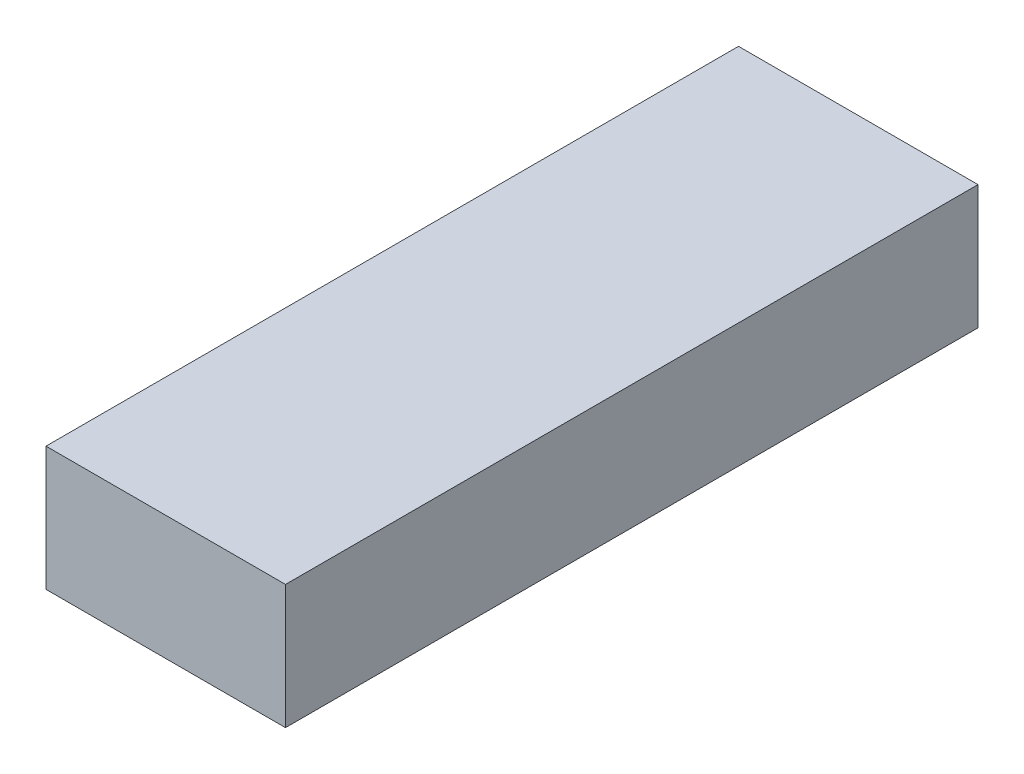
SolidWorks part; units mm, degrees
ref_plane "Front Plane" through (0, 0, 0) normal (0, 0, 1) x (1, 0, 0)
ref_plane "Top Plane" through (0, 0, 0) normal (0, 1, 0) x (1, 0, 0)
ref_plane "Right Plane" through (0, 0, 0) normal (1, 0, 0) x (0, 0, -1)
sketch "Sketch1" plane through (0, 0, 0) normal (0, 0, 1) x (1, 0, 0)
  line L1 (-16.6, -8.6) -> (16.6, -8.6)
  line L2 (-16.6, -8.6) -> (-16.6, 8.6)
  line L3 (-16.6, 8.6) -> (16.6, 8.6)
  line L4 (16.6, -8.6) -> (16.6, 8.6)
  line L5 (-16.6, -8.6) -> (16.6, 8.6) construction
  line L6 (-16.6, 8.6) -> (16.6, -8.6) construction
  point P0 (0, 0)
  dimension "D1" = 33.2
  dimension "D2" = 17.2
extrude "Boss-Extrude1" add sketch "Sketch1" along normal blind 96
